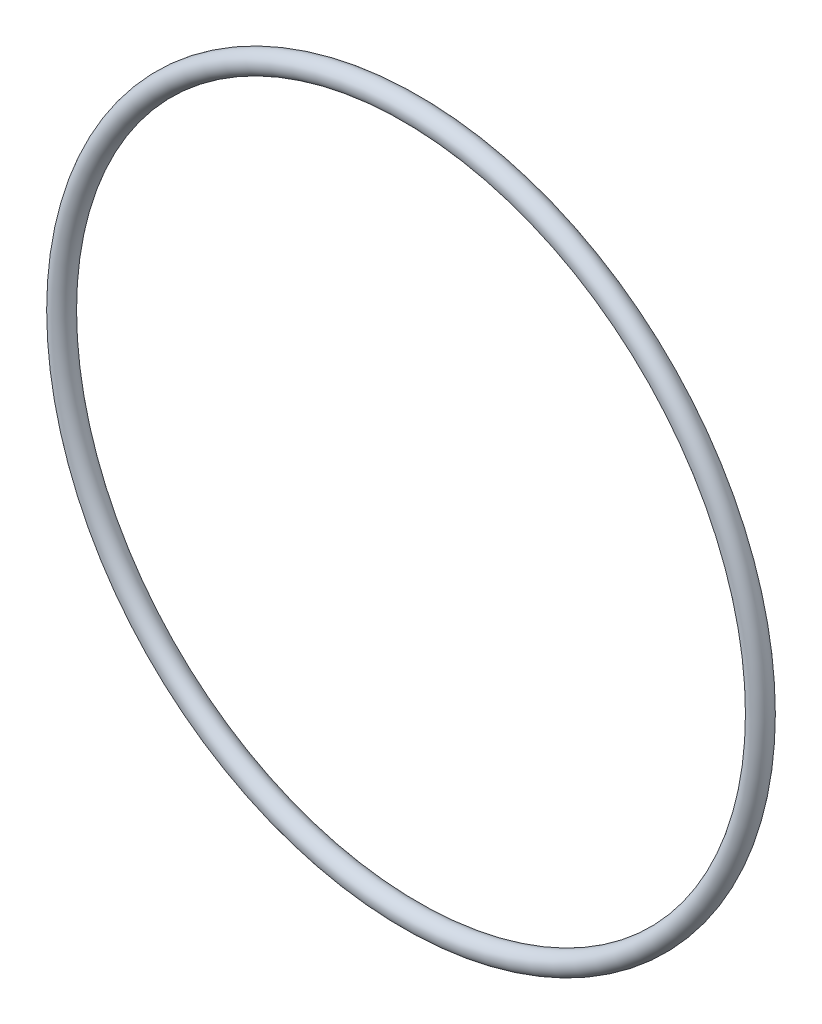
SolidWorks part; units mm, degrees
ref_plane "Front" through (0, 0, 0) normal (0, 0, 1) x (1, 0, 0)
ref_plane "Top" through (0, 0, 0) normal (0, 1, 0) x (1, 0, 0)
ref_plane "Right" through (0, 0, 0) normal (1, 0, 0) x (0, 0, -1)
sketch "Sketch1" plane through (0, 0, 0) normal (1, 0, 0) x (0, -1, 0)
  line L0 (0, -2.667) -> (0, 2.667) construction
  line L2 (-99.8157, 0) -> (99.8157, 0) construction
  line L3 (-85.4075, 0) -> (85.4075, 0) construction
  circle A0 centre (88.0745, 0) radius 2.667
  point P9 (85.4075, 0)
  point P10 (90.7415, 0)
  point P13 (88.0745, 2.667)
  point P14 (88.0745, -2.667)
  dimension "Width" = 5.334
  dimension "ID" = 170.815
revolve "Revolve1" add sketch "Sketch1" angle 360 about L0
